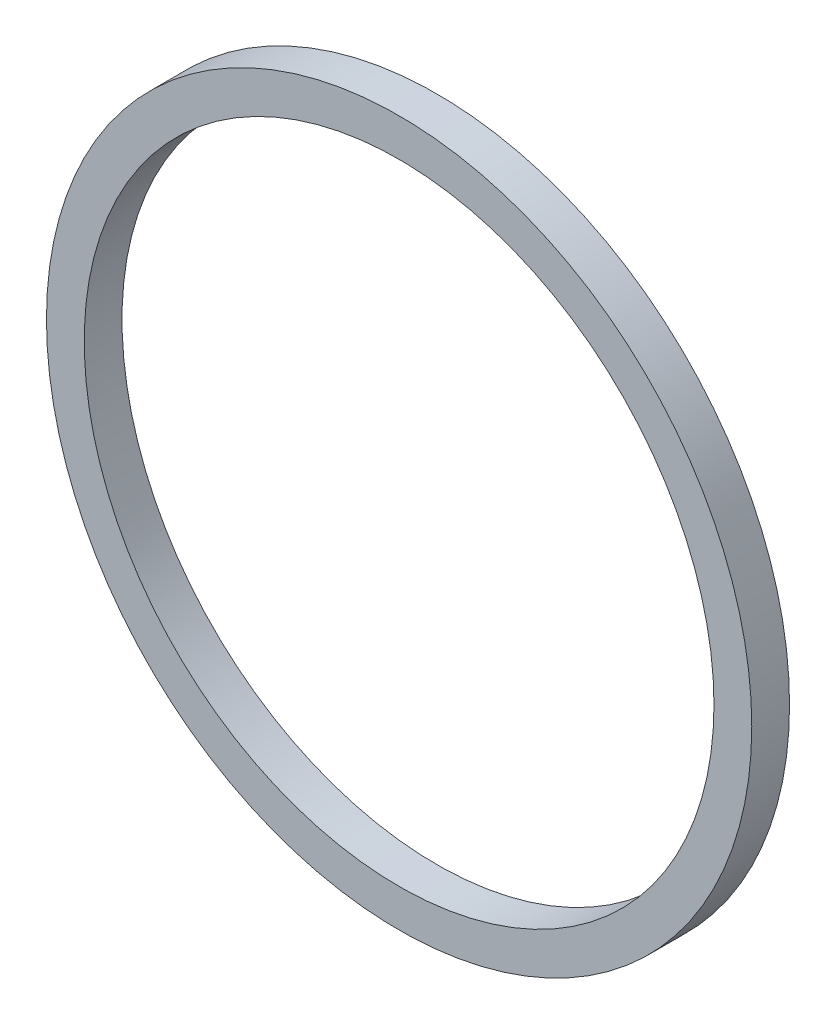
SolidWorks part; units mm, degrees
ref_plane "Front Plane" through (0, 0, 0) normal (0, 0, 1) x (1, 0, 0)
ref_plane "Top Plane" through (0, 0, 0) normal (0, 1, 0) x (1, 0, 0)
ref_plane "Right Plane" through (0, 0, 0) normal (1, 0, 0) x (0, 0, -1)
sketch "Sketch1" plane through (0, 0, 0) normal (0, 0, 1) x (1, 0, 0)
  circle A0 centre (0, 0) radius 12.5
  circle A1 centre (0, 0) radius 14
  dimension "D1" = 25
  dimension "D2" = 28
extrude "Boss-Extrude1" add sketch "Sketch1" along normal blind 1.5
